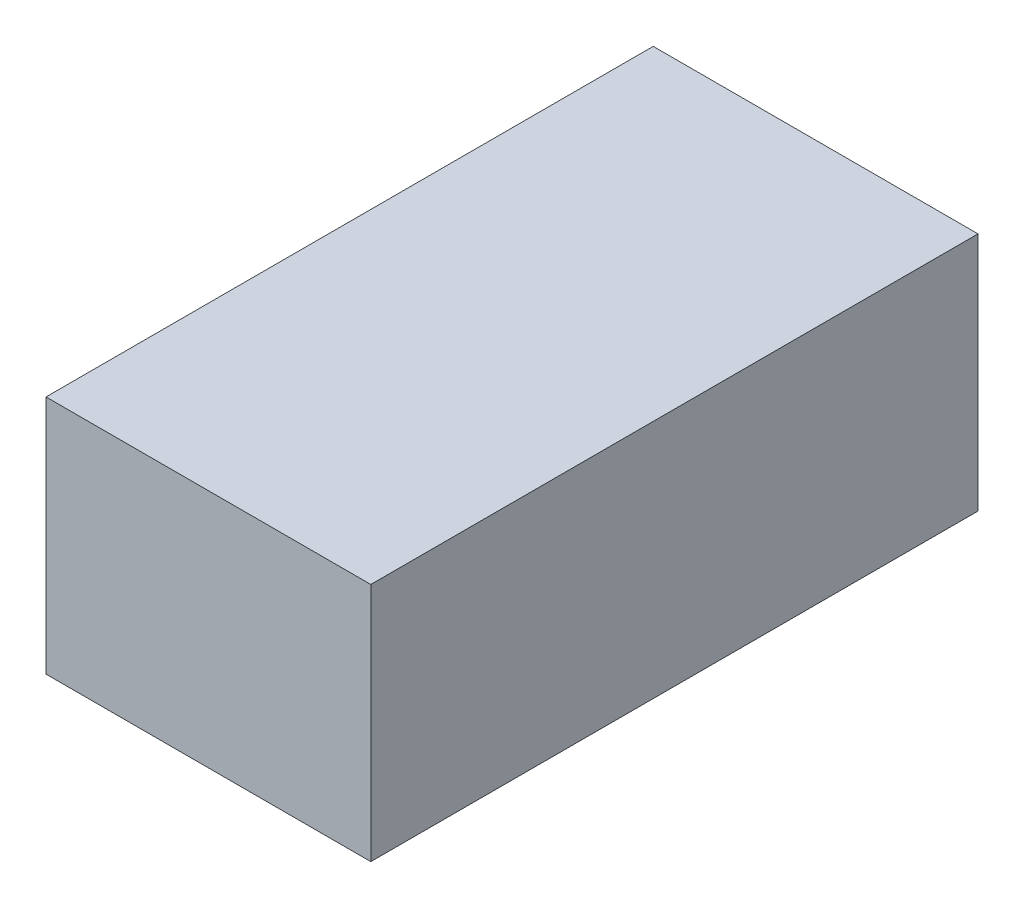
SolidWorks part; units mm, degrees
ref_plane "Front Plane" through (0, 0, 0) normal (0, 0, 1) x (1, 0, 0)
ref_plane "Top Plane" through (0, 0, 0) normal (0, 1, 0) x (1, 0, 0)
ref_plane "Right Plane" through (0, 0, 0) normal (1, 0, 0) x (0, 0, -1)
sketch "Sketch1" plane through (0, 0, 0) normal (0, 0, 1) x (1, 0, 0)
  line L1 (0, 0) -> (23, 0)
  line L2 (0, 0) -> (0, 17)
  line L3 (0, 17) -> (23, 17)
  line L4 (23, 0) -> (23, 17)
  dimension "D1" = 23
  dimension "D2" = 17
extrude "Boss-Extrude1" add sketch "Sketch1" along normal blind 43
